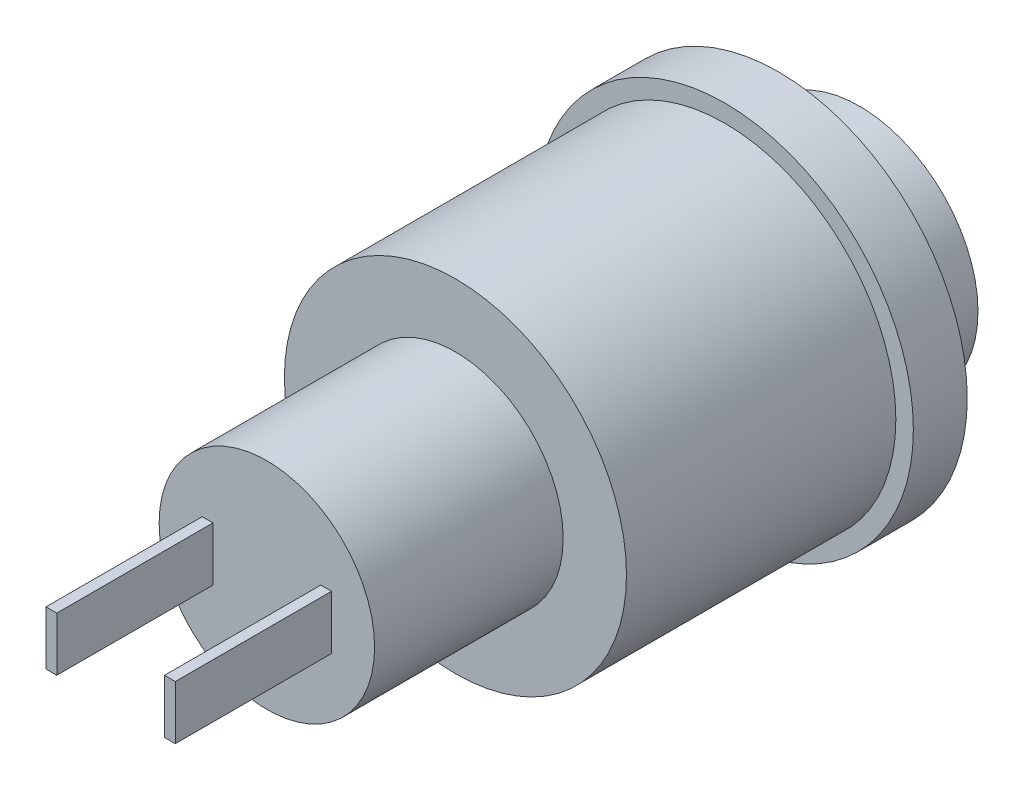
SolidWorks part; units mm, degrees
ref_plane "Plan de face" through (0, 0, 0) normal (0, 0, 1) x (1, 0, 0)
ref_plane "Plan de dessus" through (0, 0, 0) normal (0, 1, 0) x (1, 0, 0)
ref_plane "Plan de droite" through (0, 0, 0) normal (1, 0, 0) x (0, 0, -1)
sketch "Esquisse1" plane through (0, 0, 0) normal (0, 0, 1) x (1, 0, 0)
  circle A0 centre (0, 0) radius 4.4
  dimension "D1" = 8.8
extrude "Boss.-Extru.1" add sketch "Esquisse1" along normal blind 3
sketch "Esquisse2" plane through (0, 0, 3) normal (0, 0, 1) x (1, 0, 0)
  circle A0 centre (0, 0) radius 7
  dimension "D1" = 14
extrude "Boss.-Extru.2" add sketch "Esquisse2" along normal blind 2
sketch "Esquisse3" plane through (0, 0, 5) normal (0, 0, 1) x (1, 0, 0)
  circle A0 centre (0, 0) radius 6.35
  dimension "D1" = 12.7
extrude "Boss.-Extru.3" add sketch "Esquisse3" along normal blind 10
sketch "Esquisse4" plane through (0, 0, 15) normal (0, 0, 1) x (1, 0, 0)
  circle A0 centre (0, 0) radius 4
  dimension "D1" = 8
extrude "Boss.-Extru.4" add sketch "Esquisse4" along normal blind 7
sketch "Esquisse5" plane through (0, 0, 22) normal (0, 0, 1) x (1, 0, 0)
  line L0 (-2, 0) -> (2, 0) construction
  line L1 (-2.4, 1) -> (-2, 1)
  line L2 (-2.4, 1) -> (-2.4, -1)
  line L3 (-2.4, -1) -> (-2, -1)
  line L4 (-2, 1) -> (-2, -1)
  line L5 (2, 1) -> (2.4, 1)
  line L6 (2, 1) -> (2, -1)
  line L7 (2, -1) -> (2.4, -1)
  line L8 (2.4, 1) -> (2.4, -1)
  circle A0 centre (0, 0) radius 4 construction
  circle A1 centre (0, 0) radius 4 construction
  point P10 (-2.2082, -1.4625)
  point P14 (0, 0)
  point P15 (0, 0)
  dimension "D1" = 0.4
  dimension "D2" = 4
  dimension "2" = 2
extrude "Boss.-Extru.5" add sketch "Esquisse5" along normal blind 5.8
